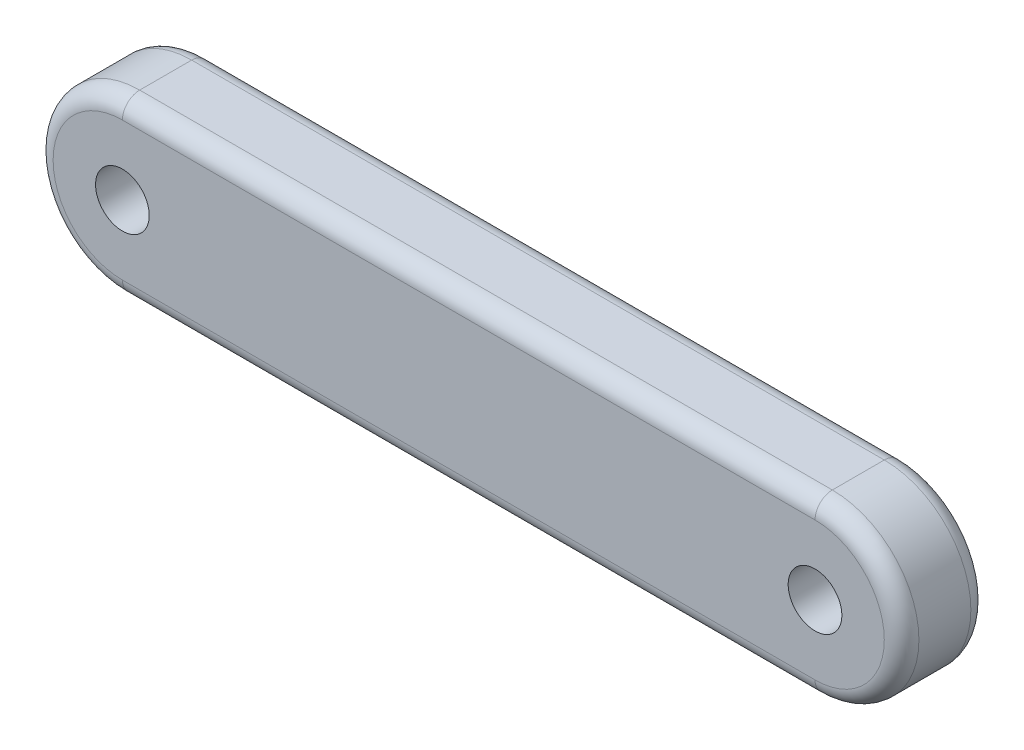
SolidWorks part; units mm, degrees
material "PET"
ref_plane "Front Plane" through (0, 0, 0) normal (0, 0, 1) x (1, 0, 0)
ref_plane "Top Plane" through (0, 0, 0) normal (0, 1, 0) x (1, 0, 0)
ref_plane "Right Plane" through (0, 0, 0) normal (1, 0, 0) x (0, 0, -1)
sketch "Sketch1" plane through (0, 0, 0) normal (0, 0, 1) x (1, 0, 0)
  line L0 (0, 0) -> (101.6, 0) construction
  line L1 (0, 12.7) -> (101.6, 12.7)
  line L2 (0, -12.7) -> (101.6, -12.7)
  arc A0 (0, 12.7) -> (0, -12.7) centre (0, 0) ccw
  arc A1 (101.6, -12.7) -> (101.6, 12.7) centre (101.6, 0) ccw
  point P3 (50.8, 0)
  dimension "D2" = 12.7
  dimension "D1" = 101.6
extrude "Boss-Extrude1" add sketch "Sketch1" along normal blind 12.7
fillet "Fillet1" radius 2.54 8 edges at (114.3, 0, 0) (50.8, -12.7, 0) (-12.7, 0, 0) (114.3, 0, 12.7) (50.8, -12.7, 12.7) (-12.7, 0, 12.7) (50.8, 12.7, 0) (50.8, 12.7, 12.7)
hole_wizard "#97 (0.31) Diameter Hole1" positions "Sketch2" profile "Sketch3" hole size "#97" standard "ANSI Inch"
sketch "Sketch2" plane through (0, 0, 12.7) normal (0, 0, 1) x (1, 0, 0)
  point P0 (0, 0)
  point P3 (101.6, 0)
sketch "Sketch3" plane through (0, 0, 12.7) normal (1, 0, 0) x (0, -1, 0)
  line L0 (0, 0) -> (0, 27.7656)
  line L1 (0, 27.7656) -> (3.937, 25.4)
  line L2 (3.937, 25.4) -> (3.937, 0)
  line L5 (3.937, 0) -> (0, 0)
  line L10 (0, 27.7656) -> (-3.937, 25.4) construction
  line L11 (0, -6.35) -> (0, 107.95) construction
  dimension "Hole Dia." = 7.874
  dimension "Hole Depth" = 25.4
  dimension "Drill Angle" = 118
